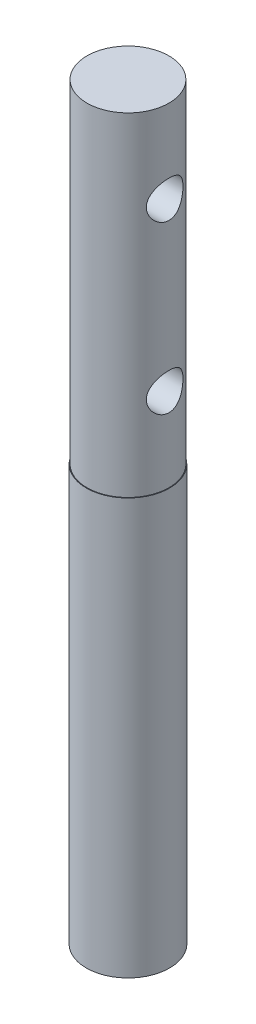
SolidWorks part; units mm, degrees
material "ASTM A36 Steel"
ref_plane "Front Plane" through (0, 0, 0) normal (0, 0, 1) x (1, 0, 0)
ref_plane "Top Plane" through (0, 0, 0) normal (0, 1, 0) x (1, 0, 0)
ref_plane "Right Plane" through (0, 0, 0) normal (1, 0, 0) x (0, 0, -1)
sketch "Sketch1" plane through (0, 0, 0) normal (0, 1, 0) x (1, 0, 0)
  circle A0 centre (0, 0) radius 25
  dimension "D1" = 50
extrude "Boss-Extrude1" add sketch "Sketch1" along normal blind 249.6
sketch "Sketch2" plane through (0, 249.6, 0) normal (0, 1, 0) x (1, 0, 0)
  circle A0 centre (0, 0) radius 24.61
  dimension "D1" = 49.22
extrude "Boss-Extrude2" add sketch "Sketch2" along normal blind 200
ref_plane "Plane1" through (25, 0, 0) normal (1, 0, 0) x (0, 0, -1)
sketch "Sketch3" plane through (0, 0, 0) normal (1, 0, 0) x (0, 0, -1)
  line L0 (25, 249.6) -> (-25, 249.6) construction
  circle A0 centre (0, 299.6) radius 11
  circle A1 centre (0, 399.6) radius 11
  dimension "D1" = 22
  dimension "D2" = 50
  dimension "D3" = 22
  dimension "D4" = 100
extrude "Cut-Extrude1" cut sketch "Sketch3" against normal through all both and the other way through all
